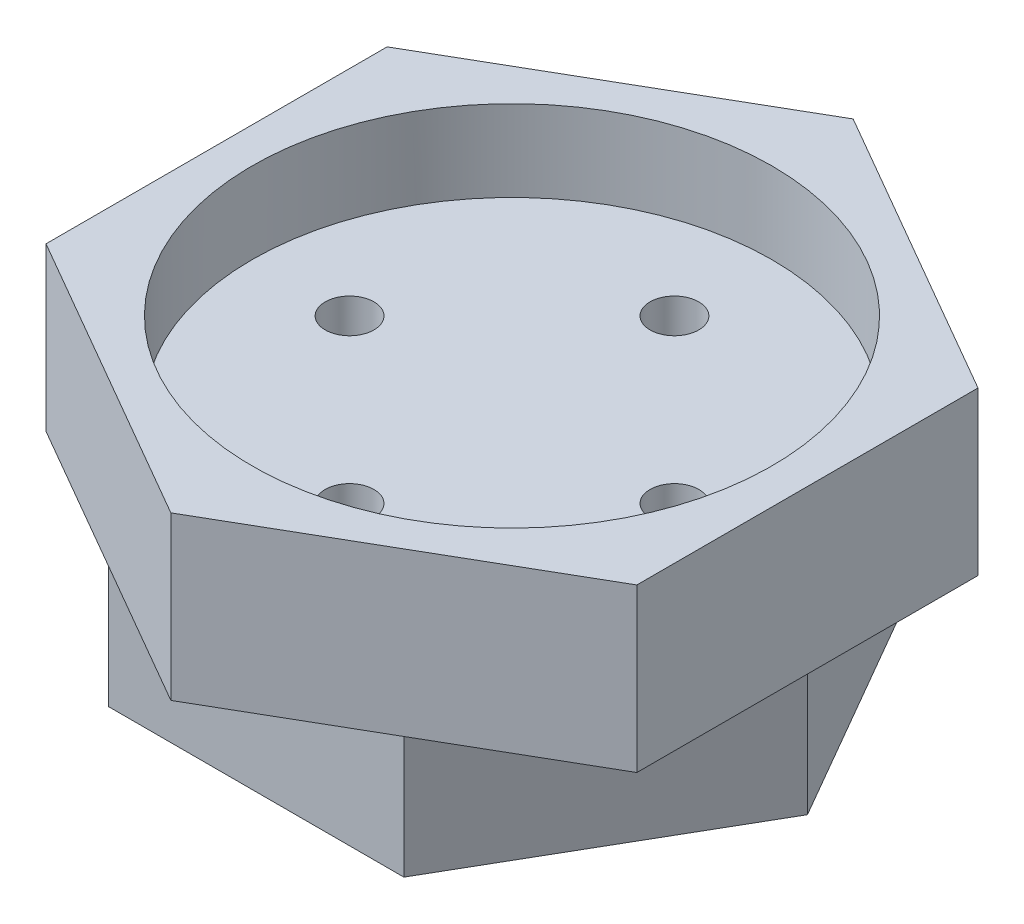
SolidWorks part; units mm, degrees
ref_plane "Front Plane" through (0, 0, 0) normal (0, 0, 1) x (1, 0, 0)
ref_plane "Top Plane" through (0, 0, 0) normal (0, 1, 0) x (1, 0, 0)
ref_plane "Right Plane" through (0, 0, 0) normal (1, 0, 0) x (0, 0, -1)
sketch "Sketch2" plane through (0, 0, 0) normal (0, 1, 0) x (1, 0, 0)
  circle A0 centre (0, 0) radius 32
  dimension "D1" = 64
extrude "Boss-Extrude1" add sketch "Sketch2" along normal blind 10
sketch "Sketch3" plane through (0, 0, 0) normal (0, -1, 0) x (1, 0, 0)
  circle A0 centre (0, 0) radius 32
  circle A1 centre (0, 0) radius 32 construction
extrude "Extrude-Thin1" add sketch "Sketch3" against normal blind 20 thin
sketch "Sketch4" plane through (0, 0, 0) normal (0, -1, 0) x (1, 0, 0)
  line L1 (36.3731, -21) -> (36.3731, 21)
  line L2 (36.3731, 21) -> (0, 42)
  line L3 (0, 42) -> (-36.3731, 21)
  line L4 (-36.3731, 21) -> (-36.3731, -21)
  line L5 (-36.3731, -21) -> (0, -42)
  line L6 (0, -42) -> (36.3731, -21)
  circle A0 centre (0, 0) radius 36.3731 construction
  circle A1 centre (0, 0) radius 42 construction
extrude "Cut-Extrude1" cut sketch "Sketch4" against normal through all flip side to cut
sketch "Sketch5" plane through (0, 0, 0) normal (0, -1, 0) x (1, 0, 0)
  line L0 (36.3731, -21) -> (36.3731, 21) construction
  line L1 (36.3731, 0) -> (18.1865, 31.5)
  line L2 (18.1865, 31.5) -> (-18.1865, 31.5)
  line L3 (-18.1865, 31.5) -> (-36.3731, 0)
  line L4 (-36.3731, 0) -> (-18.1865, -31.5)
  line L5 (-18.1865, -31.5) -> (18.1865, -31.5)
  line L6 (18.1865, -31.5) -> (36.3731, 0)
  line L7 (36.3731, 21) -> (0, 42) construction
  circle A0 centre (0, 0) radius 31.5 construction
  point P1 (45.2664, 0)
  point P12 (-58.676, -8.1234)
  point P13 (0, 0)
  point P14 (18.1865, 31.5)
extrude "Boss-Extrude2" add sketch "Sketch5" along normal blind 15
sketch "Sketch6" plane through (0, -15, 0) normal (0, -1, 0) x (1, 0, 0)
  circle A0 centre (0, 0) radius 20 construction
  circle A1 centre (0, 20) radius 3
  circle A7 centre (20, 0) radius 3
  circle A8 centre (0, -20) radius 3
  circle A9 centre (-20, 0) radius 3
  point P14 (0, 0)
  point P17 (8.6603, -5)
  dimension "D1" = 40
  dimension "D2" = 6
  dimension "D3" = 4
extrude "Cut-Extrude2" cut sketch "Sketch6" against normal through all
